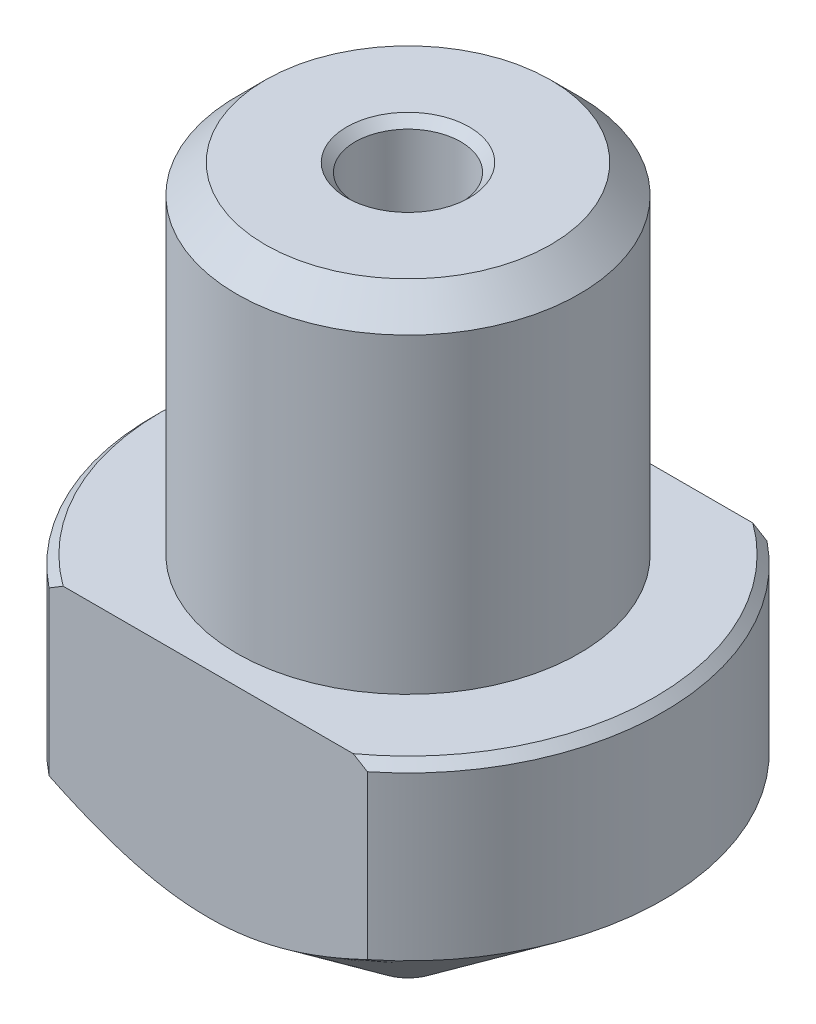
SolidWorks part; units mm, degrees
ref_plane "Front" through (0, 0, 0) normal (0, 0, 1) x (1, 0, 0)
ref_plane "Top" through (0, 0, 0) normal (0, 1, 0) x (1, 0, 0)
ref_plane "Right" through (0, 0, 0) normal (1, 0, 0) x (0, 0, -1)
sketch "Sketch1" plane through (0, 0, 0) normal (1, 0, 0) x (0, 0, -1)
  line L0 (0, 16.0512) -> (0, 0) construction
  line L1 (0, 0) -> (16.6745, 0) construction
  line L2 (0.925, -4.4387) -> (0.925, 5.95)
  line L3 (0.925, 5.95) -> (3, 5.95)
  line L4 (3, 5.95) -> (3, 0)
  line L5 (3, 0) -> (4.475, 0)
  line L6 (4.475, 0) -> (4.475, -3)
  line L7 (4.475, -3) -> (0.6, -6)
  line L8 (0.6, -6) -> (0.2, -6)
  line L9 (0.2, -6) -> (0.2, -5)
  line L10 (0.2, -5) -> (0.925, -4.4387)
  dimension "D1" = 6
  dimension "D2" = 1.85
  dimension "D3" = 3
  dimension "D4" = 6
  dimension "D5" = 8.95
  dimension "D6" = 1.2
  dimension "D7" = 0.4
  dimension "D8" = 5.95
  dimension "D9" = 1
revolve "Revolve1" add sketch "Sketch1" angle 360 about L0
cosmetic thread "Cosmetic Thread1" parameters "D2"=4.891
sketch "Sketch2" plane through (0, 0, 0) normal (0, 1, 0) x (1, 0, 0)
  line L0 (0, 4.475) -> (0, 0) construction
  line L1 (0, 0) -> (5.9459, 0) construction
  line L2 (-2.7885, -4.475) -> (-2.7885, -3.5)
  line L3 (-2.7885, 4.475) -> (2.7885, 4.475)
  line L4 (-2.7885, 4.475) -> (-2.7885, 3.5)
  line L5 (-2.7885, 3.5) -> (2.7885, 3.5)
  line L6 (2.7885, 4.475) -> (2.7885, 3.5)
  line L7 (-2.7885, -3.5) -> (2.7885, -3.5)
  line L8 (2.7885, -4.475) -> (2.7885, -3.5)
  line L9 (-2.7885, -4.475) -> (2.7885, -4.475)
  circle A0 centre (0, 0) radius 4.475 construction
  dimension "D1" = 7
extrude "Cut-Extrude1" cut sketch "Sketch2" against normal up to next
chamfer "Chamfer1" distance 0.5 angle 45 1 edges at (0, 5.95, 3)
chamfer "Chamfer2" distance 0.15 angle 45 3 edges at (0, 5.95, 0.925) (-4.475, 0, 0) (4.475, 0, 0)
